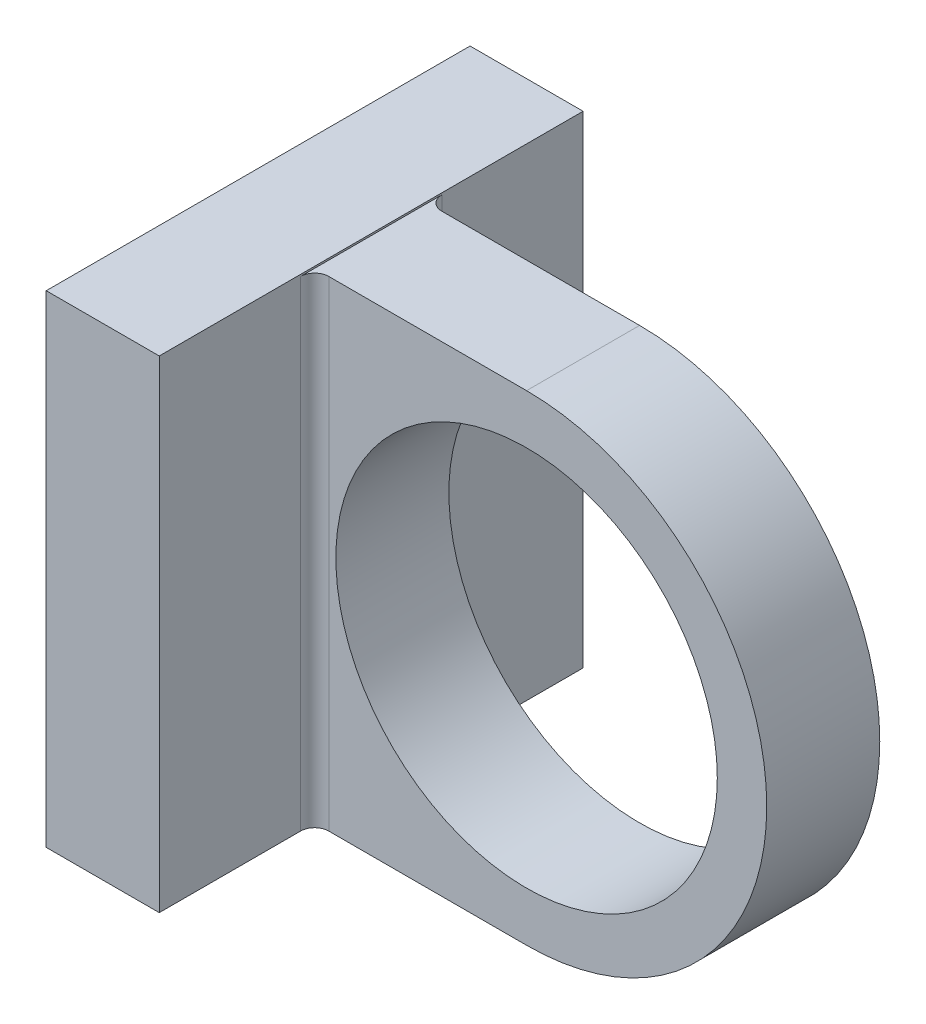
SolidWorks part; units mm, degrees
ref_plane "Front Plane" through (0, 0, 0) normal (0, 0, 1) x (1, 0, 0)
ref_plane "Top Plane" through (0, 0, 0) normal (0, 1, 0) x (1, 0, 0)
ref_plane "Right Plane" through (0, 0, 0) normal (1, 0, 0) x (0, 0, -1)
sketch "Sketch2" plane through (0, 0, 0) normal (0, 0, 1) x (1, 0, 0)
  line L4 (22.9129, 16.376) -> (22.9129, -18.1515) construction
  line L5 (22.9129, 16.1123) -> (-0.0871, 16.1123)
  line L6 (22.9129, -17.8877) -> (-0.0871, -17.8877)
  line L7 (-0.0871, 16.1123) -> (-0.0871, -17.8877)
  circle A0 centre (22.9129, -0.8877) radius 13.5
  arc A2 (22.9129, -17.8877) -> (22.9129, 16.1123) centre (22.9129, -0.8877) ccw
  dimension "D3" = 27
  dimension "D4" = 23
  dimension "D1" = 34
  dimension "D2" = 23
extrude "Boss-Extrude1" add sketch "Sketch2" along normal blind 8
sketch "Sketch3" plane through (-0.0871, 0, 0) normal (-1, 0, 0) x (0, 0, 1)
  line L0 (8, -17.8877) -> (0, -17.8877) construction
  line L1 (-11, 16.2392) -> (19, 16.2392)
  line L2 (-11, 16.2392) -> (-11, -17.8877)
  line L3 (-11, -17.8877) -> (19, -17.8877)
  line L4 (19, 16.2392) -> (19, -17.8877)
  point P4 (4, -17.8877)
  point P7 (4, -17.8877)
  dimension "D1" = 30
extrude "Boss-Extrude2" add sketch "Sketch3" against normal blind 8
fillet "Fillet1" radius 1 2 edges at (7.9129, -0.8877, 0) (7.9129, -0.8877, 8)
